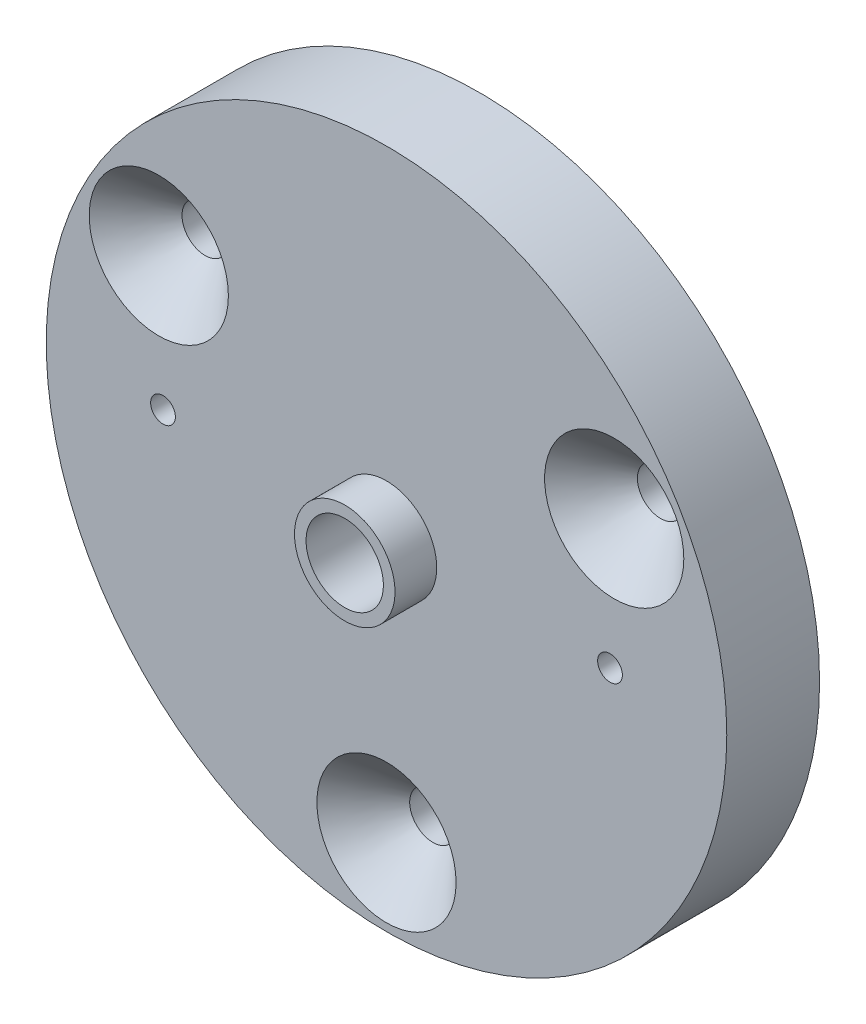
SolidWorks part; units mm, degrees
ref_plane "Спереди" through (0, 0, 0) normal (0, 0, 1) x (1, 0, 0)
ref_plane "Сверху" through (0, 0, 0) normal (0, 1, 0) x (1, 0, 0)
ref_plane "Справа" through (0, 0, 0) normal (1, 0, 0) x (0, 0, -1)
sketch "Эскиз1" plane through (0, 0, 0) normal (0, 0, 1) x (1, 0, 0)
  circle A0 centre (0, 0) radius 22
  dimension "D1" = 44
extrude "Бобышка-Вытянуть1" add sketch "Эскиз1" along normal blind 6
sketch "Эскиз2" plane through (0, 0, 6) normal (0, 0, 1) x (1, 0, 0)
  circle A0 centre (0, 0) radius 3.25
  dimension "D1" = 6.5
extrude "Бобышка-Вытянуть2" add sketch "Эскиз2" along normal blind 2.7
sketch "Эскиз3" plane through (0, 0, 8.7) normal (0, 0, 1) x (1, 0, 0)
  circle A0 centre (0, 0) radius 2.5
  dimension "D1" = 5
extrude "Вырез-Вытянуть1" cut sketch "Эскиз3" against normal through all
sketch "Эскиз4" plane through (0, 0, 6) normal (0, 0, 1) x (1, 0, 0)
  circle A0 centre (-14.45, 0) radius 0.8
  circle A1 centre (14.45, 0) radius 0.8
  dimension "D1" = 1.6
  dimension "D2" = 14.45
  dimension "D3" = 28.9
extrude "Вырез-Вытянуть2" cut sketch "Эскиз4" against normal through all
sketch "Эскиз5" plane through (0, 0, 0) normal (0, 0, -1) x (-1, 0, 0)
  circle A0 centre (0, 0) radius 13
  dimension "D1" = 26
extrude "Вырез-Вытянуть3" cut sketch "Эскиз5" against normal blind 2
sketch "Эскиз6" plane through (0, 0, 6) normal (0, 0, 1) x (1, 0, 0)
  circle A0 centre (0, -17) radius 1.5
  circle A1 centre (-14.7224, 8.5) radius 1.5
  circle A2 centre (14.7224, 8.5) radius 1.5
  point P9 (0, 0)
  dimension "D1" = 3
  dimension "D2" = 0
  dimension "D3" = 17
  dimension "D4" = 3
extrude "Вырез-Вытянуть4" cut sketch "Эскиз6" against normal through all
chamfer "Фаска1" distance 3 angle 45 3 edges at (1.5, -17, 6) (16.2224, 8.5, 6) (-13.2224, 8.5, 6)
